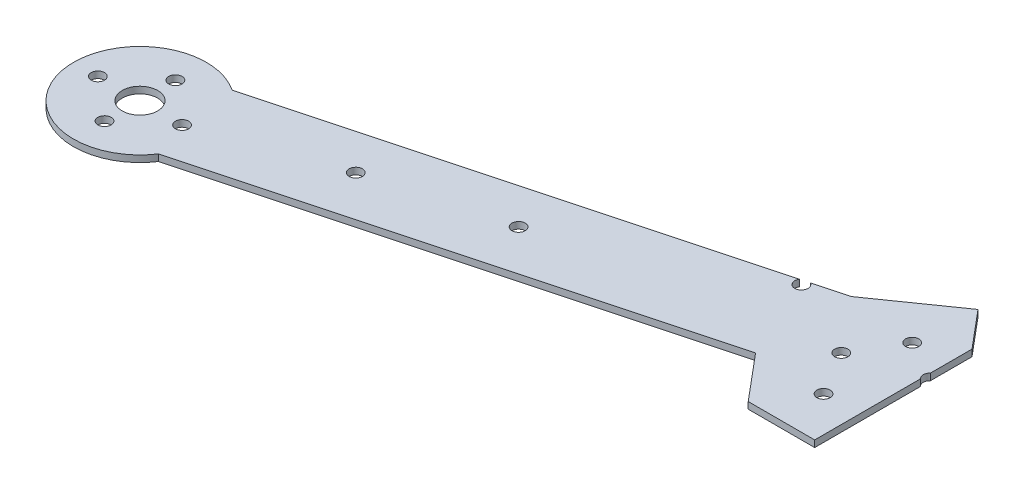
SolidWorks part; units mm, degrees
other "Markup1"
sketch "Sketch5" plane through (0, 1.5, 8.4265) normal (-0.2691, 0.6708, 0.6911) x (0.9345, 0.0084, 0.3557)
ref_plane "Front Plane" through (0, 0, 0) normal (0, 0, 1) x (1, 0, 0)
ref_plane "Top Plane" through (0, 0, 0) normal (0, 1, 0) x (1, 0, 0)
ref_plane "Right Plane" through (0, 0, 0) normal (1, 0, 0) x (0, 0, -1)
sketch "Sketch2" plane through (0, 0, 0) normal (0, 1, 0) x (1, 0, 0)
  line L7 (0, 0) -> (0, 15.3974) construction
  line L8 (-23.6776, -60.4195) -> (-23.8633, -38.593) construction
  line L9 (-136.0028, -80.5981) -> (-147.7774, -80.5981) construction
  line L10 (-147.7774, -80.5981) -> (-142.4295, -80.5981) construction
  line L11 (-142.4295, -80.5981) -> (-142.4295, -86.6558) construction
  line L12 (0, -35.2611) -> (0, -44.6431)
  line L17 (0, -70.7611) -> (-15, -70.7611)
  line L20 (-15, -70.7611) -> (-23.6776, -60.4195)
  line L23 (-23.6776, -60.4195) -> (-129.9295, -88.8896)
  line L25 (7.0707, -17.6306) -> (28.2625, -17.6306) construction
  line L51 (0, -35.2611) -> (-7.0707, -26.8346)
  line L52 (-7.0707, -26.8346) -> (-23.8633, -38.593)
  line L53 (-23.8633, -38.593) -> (-134.0979, -68.1247)
  line L54 (-142.4295, -80.5981) -> (-142.4295, -75.2609)
  line L55 (0, -46.8792) -> (0, -70.7611)
  arc A28 (-134.0979, -68.1247) -> (-129.9295, -88.8896) centre (-142.4295, -80.5981) ccw
  circle A29 centre (-142.4295, -80.5981) radius 4
  circle A30 centre (-8, -60.7611) radius 1.5
  circle A31 centre (-14, -50.7611) radius 1.5
  circle A32 centre (-8, -40.7611) radius 1.5
  arc A33 (0, -44.6431) -> (0, -46.8792) centre (1, -45.7611) ccw
  circle A42 centre (-142.4295, -72.5981) radius 1.5
  circle A43 centre (-132.9295, -80.5981) radius 1.5
  circle A44 centre (-151.9295, -80.5981) radius 1.5
  circle A45 centre (-142.4295, -88.5981) radius 1.5
  point P34 (-142.2261, -80.5981)
  point P127 (-142.4295, -80.5981)
  dimension "D8" = 9.5
  dimension "D1" = 3
  dimension "D2" = 3
  dimension "D3" = 3
  dimension "D4" = 3
  dimension "D5" = 16
  dimension "D6" = 8
  dimension "D7" = 19
extrude "Boss-Extrude1" add sketch "Sketch2" along normal blind 1.5
sketch "Sketch6" plane through (0, 1.5, 0) normal (0, 1, 0) x (1, 0, 0)
  circle A0 centre (-31.86, -41.9011) radius 1.5
  circle A1 centre (-14, -50.7611) radius 1.5 construction
  dimension "D1" = 3
  dimension "D2" = 8.86
  dimension "D3" = 17.86
extrude "Cut-Extrude1" cut sketch "Sketch6" against normal up to surface (1.5 mm away) up to face at (-142.4295, 0, 90.0981)
sketch "Sketch7" plane through (0, 1.5, 0) normal (0, 1, 0) x (1, 0, 0)
  line L0 (-134.0979, -68.1247) -> (-23.8633, -38.593) construction
  line L1 (-142.4295, -80.5981) -> (-23.8791, -48.8385) construction
  circle A0 centre (-104.0141, -70.3066) radius 1.5
  circle A1 centre (-75.036, -62.5434) radius 1.5
  dimension "D1" = 3
  dimension "D2" = 3
  dimension "D3" = 30
  dimension "D4" = 39.77
extrude "Cut-Extrude2" cut sketch "Sketch7" against normal up to surface (1.5 mm away) up to face at (-142.4295, 0, 90.0981)
